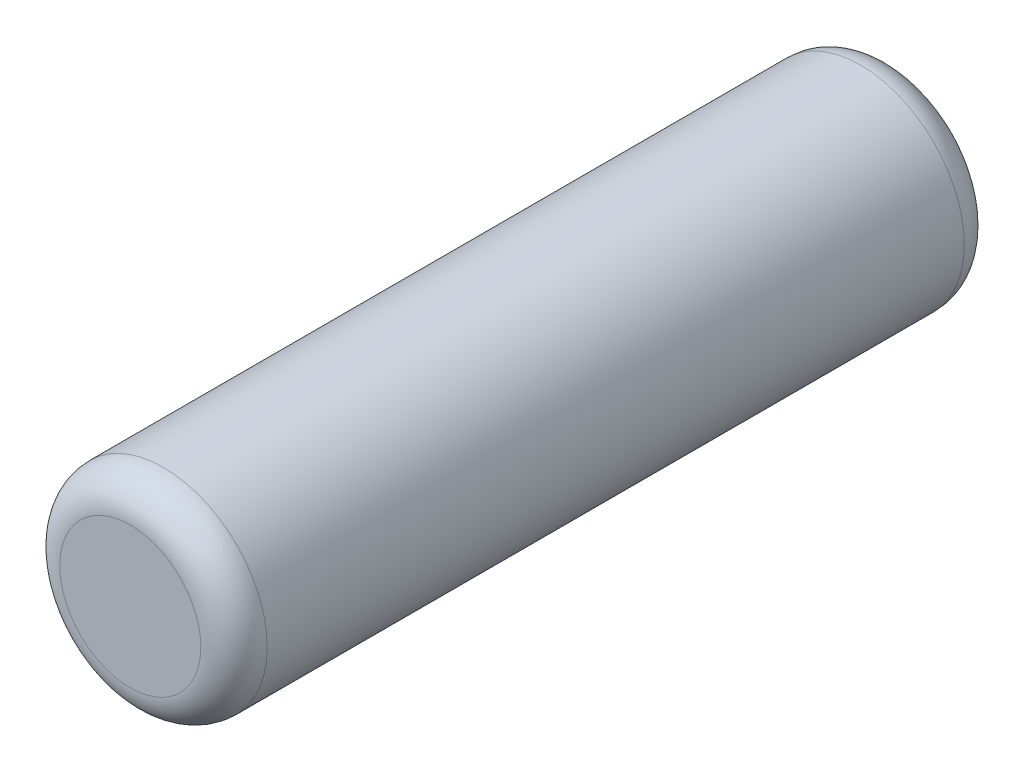
SolidWorks part; units mm, degrees
ref_plane "Front Plane" through (0, 0, 0) normal (0, 0, 1) x (1, 0, 0)
ref_plane "Top Plane" through (0, 0, 0) normal (0, 1, 0) x (1, 0, 0)
ref_plane "Right Plane" through (0, 0, 0) normal (1, 0, 0) x (0, 0, -1)
sketch "Sketch1" plane through (0, 0, 0) normal (0, 0, 1) x (1, 0, 0)
  circle A0 centre (0, 0) radius 6.25
  dimension "D1" = 12.5
extrude "Boss-Extrude1" add sketch "Sketch1" along normal mid plane 46
fillet "Fillet1" radius 2 2 edges at (6.25, 0, -23) (6.25, 0, 23)
